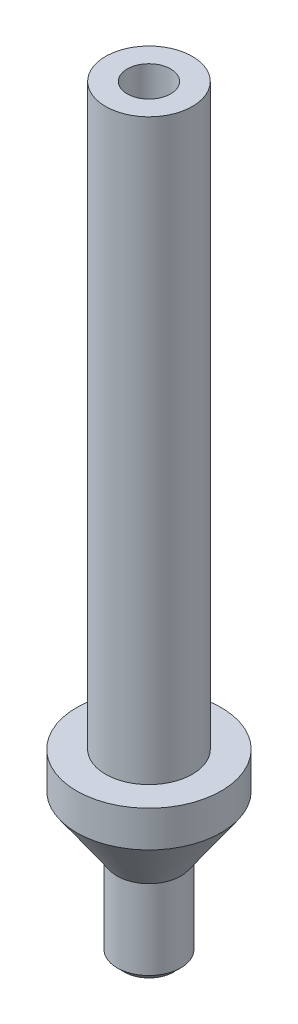
SolidWorks part; units mm, degrees
ref_plane "Front Plane" through (0, 0, 0) normal (0, 0, 1) x (1, 0, 0)
ref_plane "Top Plane" through (0, 0, 0) normal (0, 1, 0) x (1, 0, 0)
ref_plane "Right Plane" through (0, 0, 0) normal (1, 0, 0) x (0, 0, -1)
sketch "Sketch1" plane through (0, 0, 0) normal (1, 0, 0) x (0, 0, -1)
  line L0 (0, 0) -> (-2.2, 0)
  line L1 (-2.2, 0) -> (-2.2, 6.0012)
  line L3 (-5, 10) -> (-5, 12.5)
  line L4 (-5, 12.5) -> (-3, 12.5)
  line L5 (-3, 12.5) -> (-3, 52.5)
  line L6 (-3, 52.5) -> (0, 52.5)
  line L7 (0, 52.5) -> (0, 0)
  line L8 (-5, 10) -> (-2.2, 6.0012)
  line L9 (-2.2, 6.0012) -> (-10.8943, 6.0012) construction
  point P3 (0, 0)
  dimension "D1" = 3
  dimension "D3" = 40
  dimension "D4" = 2.5
  dimension "D5" = 2
  dimension "D6" = 2.2
  dimension "D8" = 55
revolve "Revolve1" add sketch "Sketch1" angle 360 about L7
sketch "Sketch2" plane through (0, 52.5, 0) normal (0, 1, 0) x (1, 0, 0)
  circle A0 centre (0, 0) radius 1.075
extrude "Cut-Extrude1" cut sketch "Sketch2" against normal through all both and the other way through all
sketch "Sketch3" plane through (0, 52.5, 0) normal (0, 1, 0) x (1, 0, 0)
  circle A0 centre (0, 0) radius 1.5
  dimension "D1" = 3
extrude "Cut-Extrude2" cut sketch "Sketch3" against normal blind 20 and the other way through all
chamfer "Chamfer1" distance 0.5 angle 45 1 edges at (0, 0, 2.2)
